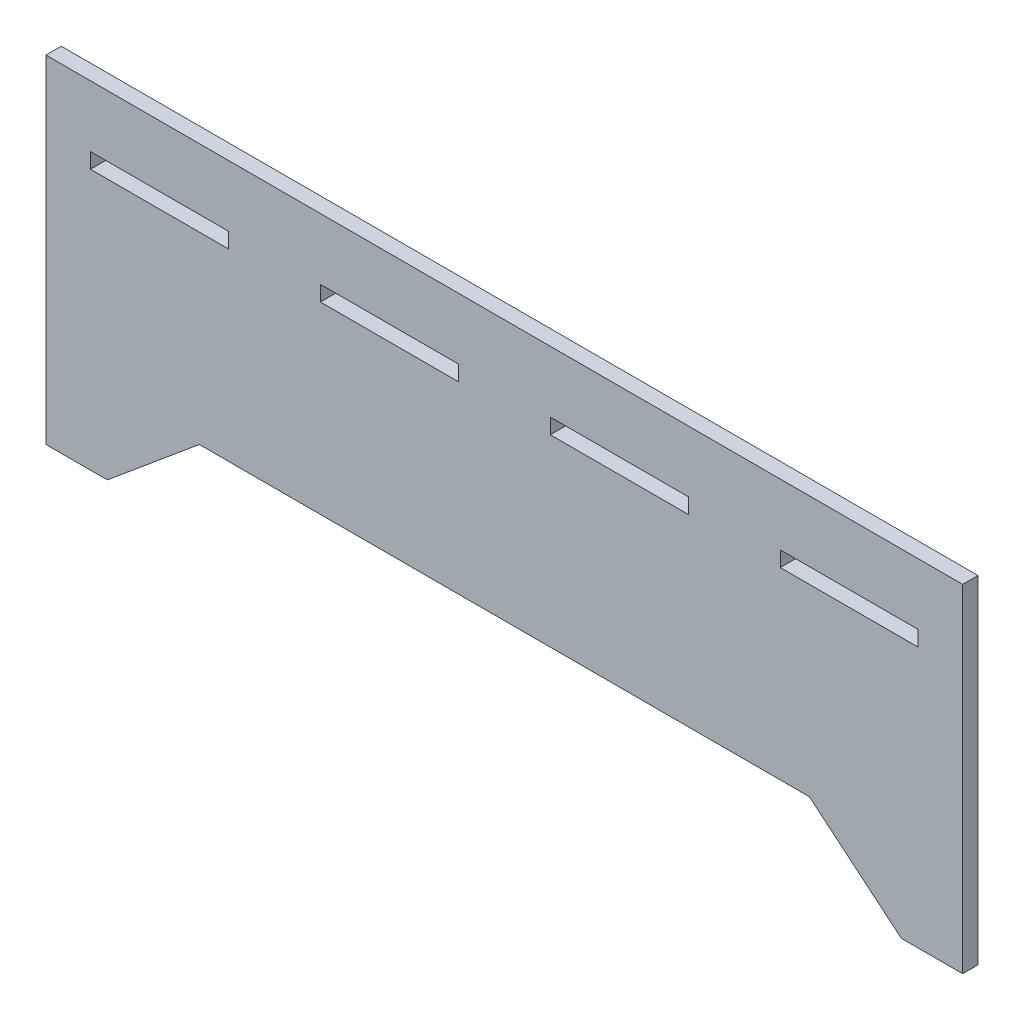
SolidWorks part; units mm, degrees
ref_plane "Plan de face" through (0, 0, 0) normal (0, 0, 1) x (1, 0, 0)
ref_plane "Plan de dessus" through (0, 0, 0) normal (0, 1, 0) x (1, 0, 0)
ref_plane "Plan de droite" through (0, 0, 0) normal (1, 0, 0) x (0, 0, -1)
sketch "Esquisse1" plane through (0, 0, 0) normal (0, 0, 1) x (1, 0, 0)
  line L0 (0, 170) -> (598, 170)
  line L1 (0, 0) -> (598, 0) construction
  line L2 (0, 0) -> (0, 170)
  line L3 (0, 130) -> (598, 130) construction
  line L4 (598, 0) -> (598, 170)
  line L5 (598, 125) -> (0, 125) construction
  line L6 (0, 120) -> (598, 120) construction
  line L7 (329, 120) -> (269, 120) construction
  line L8 (179, 130) -> (269, 130)
  line L9 (179, 130) -> (179, 120)
  line L10 (179, 120) -> (269, 120)
  line L11 (269, 130) -> (269, 120)
  line L12 (329, 130) -> (419, 130)
  line L13 (329, 130) -> (329, 120)
  line L14 (329, 120) -> (419, 120)
  line L15 (419, 130) -> (419, 120)
  line L16 (299, 120) -> (299, 130) construction
  line L17 (299, 170) -> (299, 0) construction
  line L18 (29, 130) -> (119, 130)
  line L19 (29, 130) -> (29, 120)
  line L20 (29, 120) -> (119, 120)
  line L21 (119, 130) -> (119, 120)
  line L22 (479, 130) -> (569, 130)
  line L23 (479, 130) -> (479, 120)
  line L24 (479, 120) -> (569, 120)
  line L25 (569, 130) -> (569, 120)
  line L26 (0, 0) -> (0, -50)
  line L27 (0, -50) -> (40, -50)
  line L28 (40, -50) -> (100, 0)
  line L29 (100, 0) -> (498, 0)
  line L30 (40, -50) -> (40, 0) construction
  line L31 (598, 0) -> (598, -50)
  line L32 (598, -50) -> (558, -50)
  line L33 (558, -50) -> (498, 0)
  dimension "D1" = 10
  dimension "D2" = 5
  dimension "D3" = 40
  dimension "D4" = 170
  dimension "D5" = 598
  dimension "D6" = 90
  dimension "D7" = 60
  dimension "D8" = 90
  dimension "D9" = 60
  dimension "D10" = 90
  dimension "D11" = 90
  dimension "D12" = 60
  dimension "D13" = 220
  dimension "D14" = 40
  dimension "D15" = 60
extrude "Boss.-Extru.1" add sketch "Esquisse1" along normal blind 10
